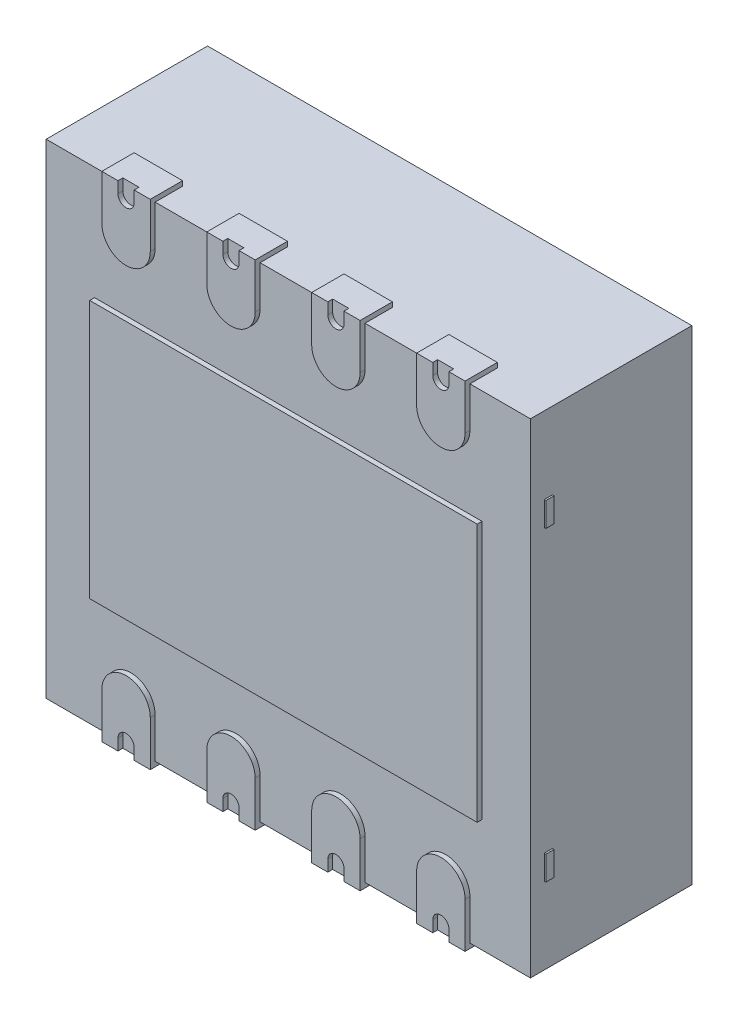
SolidWorks part; units mm, degrees
ref_plane "Front Plane" through (0, 0, 0) normal (0, 0, 1) x (1, 0, 0)
ref_plane "Top Plane" through (0, 0, 0) normal (0, 1, 0) x (1, 0, 0)
ref_plane "Right Plane" through (0, 0, 0) normal (1, 0, 0) x (0, 0, -1)
sketch "Sketch1" plane through (0, 0, 0) normal (0, 0, 1) x (1, 0, 0)
  line L1 (1.5, 1.5) -> (-1.5, 1.5)
  line L2 (1.5, 1.5) -> (1.5, -1.5)
  line L3 (1.5, -1.5) -> (-1.5, -1.5)
  line L4 (-1.5, 1.5) -> (-1.5, -1.5)
  line L5 (1.5, 1.5) -> (-1.5, -1.5) construction
  line L6 (1.5, -1.5) -> (-1.5, 1.5) construction
  point P0 (0, 0)
  dimension "D1" = 3
  dimension "D2" = 3
extrude "Boss-Extrude1" add sketch "Sketch1" against normal blind 1
sketch "Sketch2" plane through (0, 0, 0) normal (0, 0, 1) x (-1, 0, 0)
  line L0 (-0.975, 1.25) -> (-0.975, 1.6035) construction
  line L1 (1.2, 0.8) -> (-1.2, 0.8)
  line L2 (1.2, 0.8) -> (1.2, -0.8)
  line L3 (1.2, -0.8) -> (-1.2, -0.8)
  line L4 (-1.2, 0.8) -> (-1.2, -0.8)
  line L5 (1.2, 0.8) -> (-1.2, -0.8) construction
  line L6 (1.2, -0.8) -> (-1.2, 0.8) construction
  line L7 (-1.125, 1.25) -> (-1.125, 1.6035)
  line L8 (-0.825, 1.25) -> (-0.825, 1.6035)
  line L9 (1.5, 1.5) -> (-1.5, 1.5) construction
  line L10 (-0.175, 1.25) -> (-0.175, 1.6035)
  line L11 (-0.475, 1.25) -> (-0.475, 1.6035)
  line L12 (-0.325, 1.25) -> (-0.325, 1.6035) construction
  line L13 (0.475, 1.25) -> (0.475, 1.6035)
  line L14 (0.175, 1.25) -> (0.175, 1.6035)
  line L15 (0.325, 1.25) -> (0.325, 1.6035) construction
  line L16 (1.125, 1.25) -> (1.125, 1.6035)
  line L17 (0.825, 1.25) -> (0.825, 1.6035)
  line L18 (0.975, 1.25) -> (0.975, 1.6035) construction
  line L19 (0, 0) -> (0.825, 0) construction
  line L20 (-0.975, -1.25) -> (-0.975, -1.6035) construction
  line L21 (-1.125, -1.25) -> (-1.125, -1.6035)
  line L22 (-0.825, -1.25) -> (-0.825, -1.6035)
  line L23 (-0.325, -1.25) -> (-0.325, -1.6035) construction
  line L24 (-0.475, -1.25) -> (-0.475, -1.6035)
  line L25 (-0.175, -1.25) -> (-0.175, -1.6035)
  line L26 (0.325, -1.25) -> (0.325, -1.6035) construction
  line L27 (0.175, -1.25) -> (0.175, -1.6035)
  line L28 (0.475, -1.25) -> (0.475, -1.6035)
  line L29 (0.975, -1.25) -> (0.975, -1.6035) construction
  line L30 (0.825, -1.25) -> (0.825, -1.6035)
  line L31 (1.125, -1.25) -> (1.125, -1.6035)
  arc A0 (-1.125, 1.25) -> (-0.825, 1.25) centre (-0.975, 1.25) ccw
  arc A1 (-0.825, 1.6035) -> (-1.125, 1.6035) centre (-0.975, 1.6035) ccw
  arc A2 (-0.475, 1.25) -> (-0.175, 1.25) centre (-0.325, 1.25) ccw
  arc A3 (-0.175, 1.6035) -> (-0.475, 1.6035) centre (-0.325, 1.6035) ccw
  arc A4 (0.175, 1.25) -> (0.475, 1.25) centre (0.325, 1.25) ccw
  arc A5 (0.475, 1.6035) -> (0.175, 1.6035) centre (0.325, 1.6035) ccw
  arc A6 (0.825, 1.25) -> (1.125, 1.25) centre (0.975, 1.25) ccw
  arc A7 (1.125, 1.6035) -> (0.825, 1.6035) centre (0.975, 1.6035) ccw
  arc A8 (-1.125, -1.25) -> (-0.825, -1.25) centre (-0.975, -1.25) cw
  arc A9 (-0.825, -1.6035) -> (-1.125, -1.6035) centre (-0.975, -1.6035) cw
  arc A10 (-0.475, -1.25) -> (-0.175, -1.25) centre (-0.325, -1.25) cw
  arc A11 (-0.175, -1.6035) -> (-0.475, -1.6035) centre (-0.325, -1.6035) cw
  arc A12 (0.175, -1.25) -> (0.475, -1.25) centre (0.325, -1.25) cw
  arc A13 (0.475, -1.6035) -> (0.175, -1.6035) centre (0.325, -1.6035) cw
  arc A14 (0.825, -1.25) -> (1.125, -1.25) centre (0.975, -1.25) cw
  arc A15 (1.125, -1.6035) -> (0.825, -1.6035) centre (0.975, -1.6035) cw
  point P0 (0, 0)
  point P8 (-0.975, 1.4268)
  point P13 (-0.975, 1.1)
  point P19 (-0.325, 1.4268)
  point P26 (0.325, 1.4268)
  point P33 (0.975, 1.4268)
  point P41 (-0.975, -1.4268)
  point P48 (-0.325, -1.4268)
  point P55 (0.325, -1.4268)
  point P62 (0.975, -1.4268)
  dimension "D1" = 1.6
  dimension "D2" = 2.4
  dimension "D3" = 0.3
  dimension "D4" = 0.4
  dimension "D5" = 0.975
  dimension "D6" = 4
extrude "Boss-Extrude2" add sketch "Sketch2" along normal blind 0.03
sketch "Sketch4" plane through (0, 0, -1) normal (0, 0, -1) x (-1, 0, 0)
  line L1 (1.5, 1.5) -> (-1.5, 1.5)
  line L2 (1.5, 1.5) -> (1.5, -1.5)
  line L3 (1.5, -1.5) -> (-1.5, -1.5)
  line L4 (-1.5, 1.5) -> (-1.5, -1.5)
  line L5 (-2.0468, 1.8988) -> (1.8937, 1.8988)
  line L6 (-2.0468, 1.8988) -> (-2.0468, -1.9448)
  line L7 (-2.0468, -1.9448) -> (1.8937, -1.9448)
  line L8 (1.8937, 1.8988) -> (1.8937, -1.9448)
extrude "Cut-Extrude1" cut sketch "Sketch4" against normal blind 60.05
sketch "Sketch7" plane through (0, -1.5, 0) normal (0, -1, 0) x (1, 0, 0)
  line L0 (0.825, 0.03) -> (0.825, 0) construction
  line L1 (1.125, -0.17) -> (0.825, -0.17)
  line L2 (1.125, -0.17) -> (1.125, 0.03)
  line L3 (1.125, 0.03) -> (0.825, 0.03)
  line L4 (0.825, -0.17) -> (0.825, 0.03)
  line L5 (0.175, 0.03) -> (0.175, 0) construction
  line L6 (0.475, -0.17) -> (0.175, -0.17)
  line L7 (0.475, -0.17) -> (0.475, 0.03)
  line L8 (0.475, 0.03) -> (0.175, 0.03)
  line L9 (0.175, -0.17) -> (0.175, 0.03)
  line L10 (-0.475, 0.03) -> (-0.475, 0) construction
  line L11 (-0.175, -0.17) -> (-0.475, -0.17)
  line L12 (-0.175, -0.17) -> (-0.175, 0.03)
  line L13 (-0.175, 0.03) -> (-0.475, 0.03)
  line L14 (-0.475, -0.17) -> (-0.475, 0.03)
  line L15 (-1.125, 0.03) -> (-1.125, 0) construction
  line L16 (-0.825, -0.17) -> (-1.125, -0.17)
  line L17 (-0.825, -0.17) -> (-0.825, 0.03)
  line L18 (-0.825, 0.03) -> (-1.125, 0.03)
  line L19 (-1.125, -0.17) -> (-1.125, 0.03)
  point P7 (0.825, 0.015)
  point P22 (-0.475, 0.015)
  dimension "D1" = 0
  dimension "D2" = 0
  dimension "D3" = 0
  dimension "D4" = 0
  dimension "D5" = 0.2
  dimension "D6" = 0.2
  dimension "D7" = 0.2
  dimension "D8" = 0.2
extrude "Boss-Extrude3" add sketch "Sketch7" along normal blind 0.03
mirror "Mirror1" about plane through (0, 0, 0) normal (0, 1, 0) of "Boss-Extrude3"
sketch "Sketch8" plane through (0, 0, 0.03) normal (0, 0, 1) x (-1, 0, 0)
  line L0 (-0.975, 1.6098) -> (-0.975, 1.4598) construction
  line L1 (-0.925, 1.6098) -> (-0.925, 1.4598)
  line L2 (-1.025, 1.6098) -> (-1.025, 1.4598)
  line L3 (-0.375, 1.6098) -> (-0.375, 1.4598)
  line L6 (-0.275, 1.6098) -> (-0.275, 1.4598)
  line L9 (-0.325, 1.6098) -> (-0.325, 1.4598) construction
  line L13 (0.275, 1.6098) -> (0.275, 1.4598)
  line L15 (0.375, 1.6098) -> (0.375, 1.4598)
  line L16 (0.325, 1.6098) -> (0.325, 1.4598) construction
  line L17 (0.925, 1.6098) -> (0.925, 1.4598)
  line L18 (1.025, 1.6098) -> (1.025, 1.4598)
  line L19 (0.975, 1.6098) -> (0.975, 1.4598) construction
  line L20 (0, 0) -> (0.4114, 0) construction
  line L21 (-0.975, -1.6098) -> (-0.975, -1.4598) construction
  line L22 (-0.925, -1.6098) -> (-0.925, -1.4598)
  line L23 (-1.025, -1.6098) -> (-1.025, -1.4598)
  line L24 (-0.325, -1.6098) -> (-0.325, -1.4598) construction
  line L25 (-0.275, -1.6098) -> (-0.275, -1.4598)
  line L26 (-0.375, -1.6098) -> (-0.375, -1.4598)
  line L27 (0.325, -1.6098) -> (0.325, -1.4598) construction
  line L28 (0.375, -1.6098) -> (0.375, -1.4598)
  line L29 (0.275, -1.6098) -> (0.275, -1.4598)
  line L30 (0.975, -1.6098) -> (0.975, -1.4598) construction
  line L31 (1.025, -1.6098) -> (1.025, -1.4598)
  line L32 (0.925, -1.6098) -> (0.925, -1.4598)
  arc A0 (-0.925, 1.6098) -> (-1.025, 1.6098) centre (-0.975, 1.6098) ccw
  arc A1 (-1.025, 1.4598) -> (-0.925, 1.4598) centre (-0.975, 1.4598) ccw
  arc A8 (-0.275, 1.6098) -> (-0.375, 1.6098) centre (-0.325, 1.6098) ccw
  arc A9 (-0.375, 1.4598) -> (-0.275, 1.4598) centre (-0.325, 1.4598) ccw
  arc A10 (0.375, 1.6098) -> (0.275, 1.6098) centre (0.325, 1.6098) ccw
  arc A11 (0.275, 1.4598) -> (0.375, 1.4598) centre (0.325, 1.4598) ccw
  arc A12 (1.025, 1.6098) -> (0.925, 1.6098) centre (0.975, 1.6098) ccw
  arc A13 (0.925, 1.4598) -> (1.025, 1.4598) centre (0.975, 1.4598) ccw
  arc A14 (-0.925, -1.6098) -> (-1.025, -1.6098) centre (-0.975, -1.6098) cw
  arc A15 (-1.025, -1.4598) -> (-0.925, -1.4598) centre (-0.975, -1.4598) cw
  arc A16 (-0.275, -1.6098) -> (-0.375, -1.6098) centre (-0.325, -1.6098) cw
  arc A17 (-0.375, -1.4598) -> (-0.275, -1.4598) centre (-0.325, -1.4598) cw
  arc A18 (0.375, -1.6098) -> (0.275, -1.6098) centre (0.325, -1.6098) cw
  arc A19 (0.275, -1.4598) -> (0.375, -1.4598) centre (0.325, -1.4598) cw
  arc A20 (1.025, -1.6098) -> (0.925, -1.6098) centre (0.975, -1.6098) cw
  arc A21 (0.925, -1.4598) -> (1.025, -1.4598) centre (0.975, -1.4598) cw
  point P2 (-0.975, 1.5348)
  point P11 (-0.325, 1.5348)
  point P18 (0.325, 1.5348)
  point P25 (0.975, 1.5348)
  point P32 (-0.975, -1.5348)
  point P40 (-0.325, -1.5348)
  point P47 (0.325, -1.5348)
  point P54 (0.975, -1.5348)
  dimension "D1" = 0.05
  dimension "D2" = 4
  dimension "D3" = 0.15
extrude "Cut-Extrude2" cut sketch "Sketch8" against normal blind 0.03
sketch "Sketch9" plane through (-1.5, 0, 0) normal (-1, 0, 0) x (0, 0, 1)
  line L0 (0, 0) -> (-0.4231, 0) construction
  line L1 (-0.0858, 1.0236) -> (-0.0858, 0.8736)
  line L2 (-0.0858, 1.0236) -> (-0.1358, 1.0236)
  line L3 (-0.1358, 1.0236) -> (-0.1358, 0.8736)
  line L4 (-0.0858, 0.8736) -> (-0.1358, 0.8736)
  line L5 (-0.0858, -0.8736) -> (-0.1358, -0.8736)
  line L6 (-0.1358, -1.0236) -> (-0.1358, -0.8736)
  line L7 (-0.0858, -1.0236) -> (-0.1358, -1.0236)
  line L8 (-0.0858, -1.0236) -> (-0.0858, -0.8736)
  dimension "D1" = 0.15
  dimension "D2" = 0.05
extrude "Boss-Extrude4" add sketch "Sketch9" along normal blind 0.01
mirror "Mirror2" about plane through (0, 0, 0) normal (1, 0, 0) of "Boss-Extrude4"
sketch "Sketch11" plane through (0, 0, -1) normal (0, 0, -1) x (-1, 0, 0)
  line L0 (70.7212, 256.2979) -> (518.7212, 256.2979) construction
  line L54 (-0.8059, 1.0381) -> (-0.4233, 0.6054)
  line L55 (-0.3623, 0.9997) -> (-0.1188, 0.9997)
  line L56 (0.473, 0.2478) -> (0.2316, 0.2478)
  line L57 (-0.4233, 1.0381) -> (-0.0972, 1.0381)
  line L58 (-0.7882, 0.654) -> (-0.7882, 0.2148)
  line L59 (-0.1188, 0.9997) -> (0.0552, 0.7211)
  line L60 (-0.0933, 0.2106) -> (-0.3961, 0.2106)
  line L61 (-0.7882, 0.2148) -> (-1.0676, 0.2148)
  line L62 (0.5173, 0.9997) -> (0.9108, 0.9942)
  line L63 (0.5012, 0.8902) -> (0.5012, 0.6704)
  line L64 (0.9437, 0.5264) -> (0.5435, 0.5264)
  line L65 (-1.0282, 0.2545) -> (-1.0282, 0.9912)
  line L66 (0.5397, 0.8504) -> (0.8294, 0.8504)
  line L67 (1.0527, 0.8482) -> (1.0507, 0.7013)
  line L68 (0.8774, 0.8024) -> (0.8774, 0.7608)
  line L69 (-1.0676, 0.2148) -> (-1.0676, 1.0381)
  line L70 (0.5435, 0.2064) -> (0.2018, 0.2064)
  line L71 (-0.1256, 0.6262) -> (-0.3623, 0.9997)
  line L72 (0.5012, 0.5594) -> (0.5012, 0.27)
  line L73 (0.2018, 1.0381) -> (0.9437, 1.0381)
  line L74 (-0.3744, 0.4818) -> (-0.3744, 0.9397)
  line L75 (0.2391, 0.6223) -> (0.473, 0.2478)
  line L76 (0.2018, 0.2064) -> (0.0526, 0.4469)
  line L77 (-0.3981, 0.2613) -> (-0.8255, 0.7578)
  line L78 (0.2887, 0.6223) -> (0.5173, 0.9997)
  line L79 (0.8742, 0.6704) -> (0.5012, 0.6704)
  line L80 (1.0877, 0.8941) -> (1.0877, 0.6704)
  line L81 (-0.3961, 0.2106) -> (-0.7882, 0.654)
  line L82 (0.0552, 0.5301) -> (-0.1126, 0.2502)
  line L83 (0.0526, 0.7966) -> (0.2018, 1.0381)
  line L84 (0.0552, 0.7211) -> (0.2223, 0.9997)
  line L85 (-0.3623, 0.2502) -> (-0.1256, 0.6262)
  line L86 (-0.3744, 0.9397) -> (-0.1788, 0.6262)
  line L87 (0.2223, 0.9997) -> (0.4653, 0.9997)
  line L88 (0.5397, 0.8504) -> (0.5397, 0.7128)
  line L89 (-0.1126, 0.2502) -> (-0.3623, 0.2502)
  line L90 (0.5397, 0.7128) -> (0.8294, 0.7128)
  line L91 (0.2316, 0.2478) -> (0.0552, 0.5301)
  line L92 (0.5012, 0.8902) -> (0.8742, 0.8902)
  line L93 (0.5435, 0.5264) -> (0.5435, 0.2064)
  line L94 (-0.8129, 0.9912) -> (-0.3744, 0.4818)
  line L95 (0.9222, 0.8422) -> (0.9222, 0.7184)
  line L96 (-0.0972, 1.0381) -> (0.0526, 0.7966)
  line L97 (0.0526, 0.4469) -> (-0.0933, 0.2106)
  line L98 (-0.8255, 0.2545) -> (-1.0282, 0.2545)
  line L99 (0.9067, 0.5594) -> (0.5012, 0.5594)
  line L100 (-1.0676, 1.0381) -> (-0.8059, 1.0381)
  line L101 (-0.1788, 0.6262) -> (-0.3981, 0.2613)
  line L102 (0.4653, 0.9997) -> (0.2391, 0.6223)
  line L103 (-0.4233, 0.6054) -> (-0.4233, 1.0381)
  line L104 (-1.0282, 0.9912) -> (-0.8129, 0.9912)
  line L105 (-0.8255, 0.7578) -> (-0.8255, 0.2545)
  line L106 (0.5012, 0.27) -> (0.2887, 0.6223)
  arc A8 (0.8742, 0.8902) -> (0.9222, 0.8422) centre (0.8742, 0.8422) cw
  arc A9 (0.9437, 1.0381) -> (1.0877, 0.8941) centre (0.9437, 0.8941) cw
  arc A10 (0.9222, 0.7184) -> (0.8742, 0.6704) centre (0.8742, 0.7184) cw
  arc A11 (1.0877, 0.6704) -> (0.9437, 0.5264) centre (0.9437, 0.6704) cw
  arc A12 (0.8294, 0.8504) -> (0.8774, 0.8024) centre (0.8294, 0.8024) cw
  arc A13 (1.0507, 0.7013) -> (0.9067, 0.5594) centre (0.9067, 0.7034) cw
  arc A14 (0.8294, 0.7128) -> (0.8774, 0.7608) centre (0.8294, 0.7608) ccw
  arc A15 (0.9108, 0.9942) -> (1.0527, 0.8482) centre (0.9087, 0.8502) cw
sketch "Sketch12" plane through (0, 0, -1) normal (0, 0, -1) x (-1, 0, 0)
  line L0 (-1.0422, -0.9486) -> (0.9798, -0.9486) construction
  text T0 "<b>TJA1441</b>" font "Century Gothic" height 0.4
extrude "Boss-Extrude9" add sketch "Sketch11" along normal blind 0.01 contours A11 L80 A9 L73 L83 L96 L57 L103 L54 L100 L69 L61 L58 L81 L60 L97 L76 L70 L93 L64 L87 L102 L75 L56 L91 L82 L89 L85 L71 L55 L59 L84 L77 L105 L98 L65 L104 L94 L74 L86 L101 L62 A15 L67 A13 L99 L72 L106 | A10 L95 A8 L92 L63 L79 A14 L90 L88 L66 A12 L68
extrude "Boss-Extrude10" add sketch "Sketch12" along normal blind 0.01
